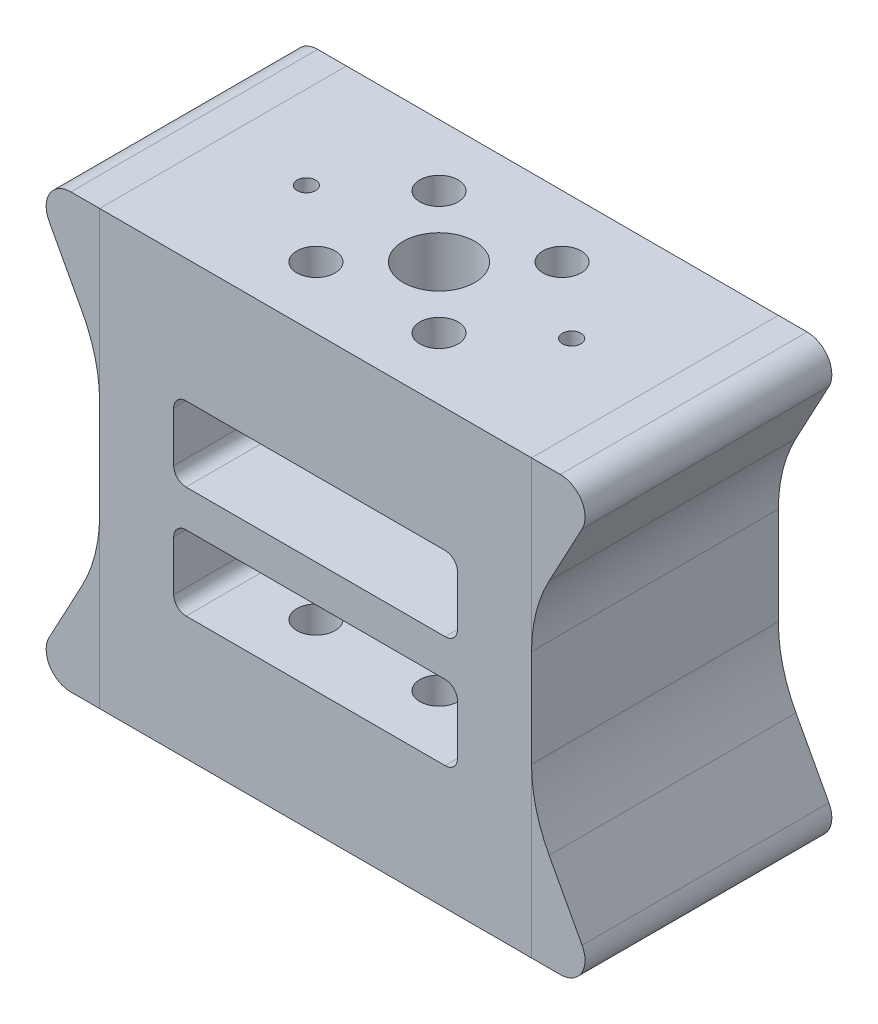
SolidWorks part; units mm, degrees
ref_plane "Front Plane" through (0, 0, 0) normal (0, 0, 1) x (1, 0, 0)
ref_plane "Top Plane" through (0, 0, 0) normal (0, 1, 0) x (1, 0, 0)
ref_plane "Right Plane" through (0, 0, 0) normal (1, 0, 0) x (0, 0, -1)
sketch "Sketch1" plane through (0, 0, 0) normal (0, 0, 1) x (1, 0, 0)
  line L1 (-15.5616, -42.5432) -> (19.4384, -42.5432)
  line L2 (-15.5616, -42.5432) -> (-15.5616, -77.6432)
  line L3 (-15.5616, -77.6432) -> (19.4384, -77.6432)
  line L4 (19.4384, -42.5432) -> (19.4384, -77.6432)
extrude "Boss-Extrude1" add sketch "Sketch1" along normal blind 16
sketch "Sketch2" plane through (0, 0, 16) normal (0, 0, 1) x (1, 0, 0)
  line L28 (-9.5616, -53.5432) -> (-9.5616, -57.5932)
  line L29 (-8.5616, -52.5432) -> (12.4384, -52.5432)
  line L30 (13.4384, -53.5432) -> (13.4384, -57.5932)
  line L31 (-8.5616, -58.5932) -> (12.4384, -58.5932)
  line L32 (-9.5616, -62.5932) -> (-9.5616, -66.6432)
  line L33 (-8.5616, -61.5932) -> (12.4384, -61.5932)
  line L34 (13.4384, -62.5932) -> (13.4384, -66.6432)
  line L35 (-8.5616, -67.6432) -> (12.4384, -67.6432)
  arc A0 (-9.5616, -66.6432) -> (-8.5616, -67.6432) centre (-8.5616, -66.6432) ccw
  arc A1 (13.4384, -66.6432) -> (12.4384, -67.6432) centre (12.4384, -66.6432) cw
  arc A2 (12.4384, -61.5932) -> (13.4384, -62.5932) centre (12.4384, -62.5932) cw
  arc A3 (13.4384, -57.5932) -> (12.4384, -58.5932) centre (12.4384, -57.5932) cw
  arc A4 (-9.5616, -57.5932) -> (-8.5616, -58.5932) centre (-8.5616, -57.5932) ccw
  arc A5 (-9.5616, -62.5932) -> (-8.5616, -61.5932) centre (-8.5616, -62.5932) cw
  arc A6 (-9.5616, -53.5432) -> (-8.5616, -52.5432) centre (-8.5616, -53.5432) cw
  arc A7 (12.4384, -52.5432) -> (13.4384, -53.5432) centre (12.4384, -53.5432) cw
  dimension "D1" = 1
ref_plane "Plane1" through (0, 0, 6) normal (0, 0, 1) x (1, 0, 0)
sketch "Sketch4" plane through (-15.5616, 0, 0) normal (-1, 0, 0) x (0, 0, 1)
  line L0 (16, -42.5432) -> (16, -77.6432) construction
  point P0 (16, -60.0932)
ref_plane "Plane2" through (0, -60.0932, 0) normal (0, 1, 0) x (1, 0, 0)
extrude "Cut-Extrude1" cut sketch "Sketch2" against normal up to next
ref_plane "Plane3" through (0, 0, 6) normal (0, 0, 1) x (1, 0, 0)
sketch "Sketch6" plane through (0, 0, 6) normal (0, 0, 1) x (1, 0, 0)
  line L1 (-16.5133, -41.7649) -> (20.6369, -41.7649)
  line L2 (-16.5133, -41.7649) -> (-16.5133, -78.73)
  line L3 (-16.5133, -78.73) -> (20.6369, -78.73)
  line L4 (20.6369, -41.7649) -> (20.6369, -78.73)
extrude "Cut-Extrude2" cut sketch "Sketch6" against normal through all
mirror "Mirror3" about plane through (0, 0, 6) normal (0, 0, 1) of bodies 111
sketch "Sketch7" plane through (0, -42.5432, 0) normal (0, 1, 0) x (1, 0, 0)
  circle A0 centre (1.9384, -6) radius 2.9
  circle A1 centre (-3.0467, -1.0149) radius 1.55
  circle A2 centre (6.9235, -1.0149) radius 1.55
  circle A3 centre (6.9235, -10.9851) radius 1.55
  circle A4 centre (-3.0467, -10.9851) radius 1.55
  point P24 (1.9384, -6)
  dimension "D1" = 3.1
  dimension "D3" = 4
extrude "Cut-Extrude3" cut sketch "Sketch7" against normal blind 12
sketch "Sketch8" plane through (0, 0, -4) normal (0, 0, -1) x (-1, 0, 0)
  line L0 (-19.4384, -77.6432) -> (-19.4384, -42.5432) construction
  point P0 (-19.4384, -60.0932)
ref_plane "Plane4" through (0, -60.0932, 0) normal (0, 1, 0) x (1, 0, 0)
sketch "Sketch9" plane through (0, 0, -4) normal (0, 0, -1) x (-1, 0, 0)
  line L0 (-19.4384, -42.5432) -> (-21.7716, -42.5432)
  line L1 (-23.5338, -45.4889) -> (-20.8649, -50.462)
  line L2 (-19.4384, -77.6432) -> (-19.4384, -42.5432) construction
  line L4 (-19.4384, -42.5432) -> (-19.4384, -77.6432)
  line L6 (15.5616, -77.6432) -> (17.8948, -77.6432)
  line L7 (-23.5338, -74.6974) -> (-20.8649, -69.7243)
  line L8 (-19.4384, -77.6432) -> (-21.7716, -77.6432)
  line L9 (19.657, -74.6974) -> (16.9881, -69.7243)
  line L11 (19.657, -45.4889) -> (16.9881, -50.462)
  line L12 (15.5616, -42.5432) -> (17.8948, -42.5432)
  line L13 (15.5616, -42.5432) -> (15.5616, -77.6432)
  arc A0 (19.657, -45.4889) -> (17.8948, -42.5432) centre (17.8948, -44.5432) ccw
  arc A1 (17.8948, -77.6432) -> (19.657, -74.6974) centre (17.8948, -75.6432) ccw
  arc A2 (-23.5338, -74.6974) -> (-21.7716, -77.6432) centre (-21.7716, -75.6432) ccw
  arc A3 (-21.7716, -42.5432) -> (-23.5338, -45.4889) centre (-21.7716, -44.5432) ccw
  arc A4 (16.9881, -69.7243) -> (15.5616, -64.0498) centre (27.5616, -64.0498) cw
  arc A5 (15.5616, -56.1366) -> (16.9881, -50.462) centre (27.5616, -56.1366) cw
  arc A6 (-20.8649, -69.7243) -> (-19.4384, -64.0498) centre (-31.4384, -64.0498) ccw
  arc A7 (-20.8649, -50.462) -> (-19.4384, -56.1366) centre (-31.4384, -56.1366) cw
  point P12 (-19.4384, -60.0932)
  point P20 (15.5616, -60.0932)
  point P33 (-19.4384, -53.12)
  line M19 (15.5616, -77.6432) -> (15.5616, -42.5432)
  line M21 (-19.4384, -42.5432) -> (-19.4384, -77.6432)
  dimension "D1" = 2
  dimension "D2" = 12
extrude "Boss-Extrude2" add sketch "Sketch9" against normal up to surface (20 mm away) contours L1 A7 L0 A3 M21 | A6 L7 A2 L8 L4 | A5 L11 A0 L12 M19 | L9 A4 L6 A1 M19 up to face at (1.9384, -64.6182, 16)
mirror "Mirror4" about plane through (0, -60.0932, 0) normal (0, 1, 0) of "Cut-Extrude3"
sketch "Sketch10" plane through (0, 0, -4) normal (0, 0, -1) x (-1, 0, 0)
  line L0 (-19.4384, -77.6432) -> (-25.1148, -77.6432)
  line L1 (15.5616, -77.6432) -> (-19.4384, -77.6432) construction
  line L2 (-20.8649, -69.7243) -> (-25.1148, -77.6432)
sketch "Sketch11" plane through (0, -42.5432, 0) normal (0, 1, 0) x (1, 0, 0)
  line L0 (19.4384, -16) -> (-15.5616, -16) construction
  circle A0 centre (12.6884, -5.9982) radius 0.75
  circle A1 centre (-8.8116, -5.9982) radius 0.75
  circle A2 centre (1.9384, -6) radius 2.9 construction
  circle A3 centre (1.9384, -6) radius 2.9 construction
  dimension "D1" = 1.5
  dimension "D2" = 1.5
  dimension "D3" = 21.5
  dimension "D4" = 10.75
  dimension "D5" = 10.75
  dimension "D6" = 10.0018
extrude "Cut-Extrude4" cut sketch "Sketch11" against normal blind 10
sketch "Sketch12" plane through (0, -77.6432, 0) normal (0, -1, 0) x (1, 0, 0)
  line L0 (-15.5616, -4) -> (19.4384, -4) construction
  circle A0 centre (12.6884, 6) radius 1.55
  circle A1 centre (-8.8116, 6) radius 1.55
  circle A3 centre (1.9384, 6) radius 2.9 construction
  circle A4 centre (1.9384, 6) radius 2.9 construction
  dimension "D1" = 3.1
  dimension "D2" = 3.1
  dimension "D3" = 10.75
  dimension "D4" = 10.75
  dimension "D5" = 21.5
  dimension "D6" = 10
extrude "Cut-Extrude5" cut sketch "Sketch12" against normal blind 10
sketch "Sketch13" plane through (0, -77.6432, 0) normal (0, -1, 0) x (1, 0, 0)
  circle A0 centre (12.6884, 6) radius 3
  circle A1 centre (-8.8116, 6) radius 3
  circle A2 centre (-8.8116, 6) radius 1.55 construction
  circle A3 centre (-8.8116, 6) radius 1.55
  circle A4 centre (12.6884, 6) radius 1.55 construction
  circle A5 centre (12.6884, 6) radius 1.55
ref_plane "Plane5" through (0, -67.6432, 0) normal (0, -1, 0) x (-1, 0, 0)
sketch "Sketch14" plane through (0, -67.6432, 0) normal (0, -1, 0) x (-1, 0, 0)
  circle A0 centre (-12.6884, -6) radius 3 construction
  circle A1 centre (-12.6884, -6) radius 3
  circle A2 centre (8.8116, -6) radius 3 construction
  circle A3 centre (8.8116, -6) radius 3
extrude "Cut-Extrude7" cut sketch "Sketch14" against normal blind 6
